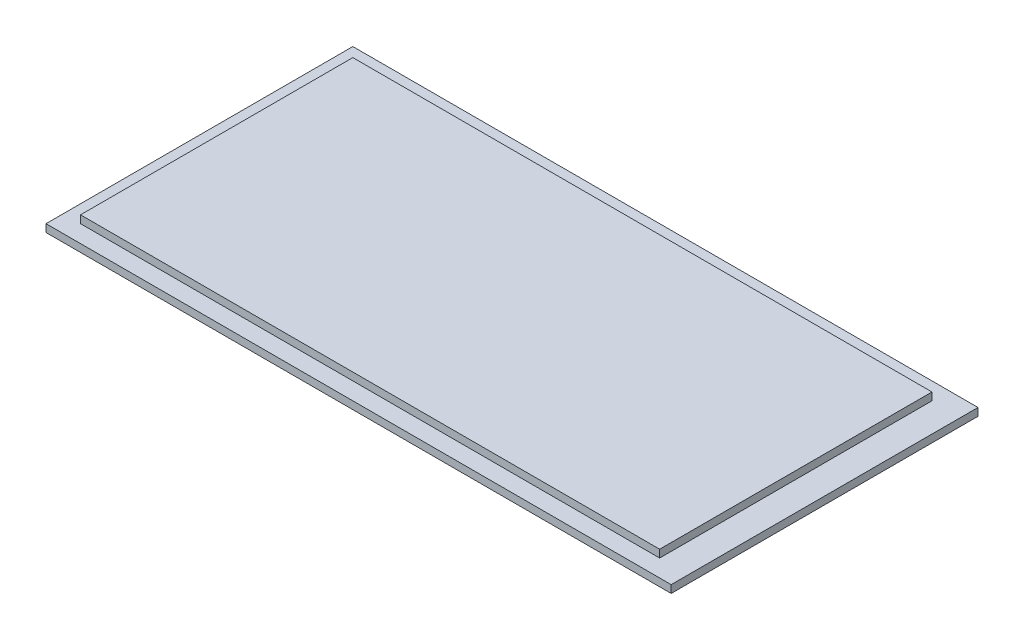
SolidWorks part; units mm, degrees
ref_plane "Ön Düzlem" through (0, 0, 0) normal (0, 0, 1) x (1, 0, 0)
ref_plane "Üst Düzlem" through (0, 0, 0) normal (0, 1, 0) x (1, 0, 0)
ref_plane "Sağ Düzlem" through (0, 0, 0) normal (1, 0, 0) x (0, 0, -1)
sketch "Çizim1" plane through (0, 0, 0) normal (0, 1, 0) x (1, 0, 0)
  line L1 (-81.5, 40) -> (81.5, 40)
  line L2 (-81.5, 40) -> (-81.5, -40)
  line L3 (-81.5, -40) -> (81.5, -40)
  line L4 (81.5, 40) -> (81.5, -40)
  line L5 (-81.5, 40) -> (81.5, -40) construction
  line L6 (-81.5, -40) -> (81.5, 40) construction
  point P0 (0, 0)
  dimension "D1" = 163
  dimension "D2" = 80
extrude "Yükseklik-Ekstrüzyon1" add sketch "Çizim1" along normal blind 2
sketch "Çizim2" plane through (0, 2, 0) normal (0, 1, 0) x (1, 0, 0)
  line L0 (-81.5, 40) -> (-81.5, -40) construction
  line L1 (-77, 35.5) -> (74, 35.5)
  line L2 (-77, 35.5) -> (-77, -35.5)
  line L3 (-77, -35.5) -> (74, -35.5)
  line L4 (74, 35.5) -> (74, -35.5)
  line L5 (-77, 35.5) -> (74, -35.5) construction
  line L6 (-77, -35.5) -> (74, 35.5) construction
  line L7 (-81.5, -40) -> (81.5, -40) construction
  point P0 (-1.5, 0)
  dimension "D1" = 151
  dimension "D2" = 71
  dimension "D3" = 4.5
  dimension "D4" = 4.5
extrude "Yükseklik-Ekstrüzyon2" add sketch "Çizim2" along normal blind 2
